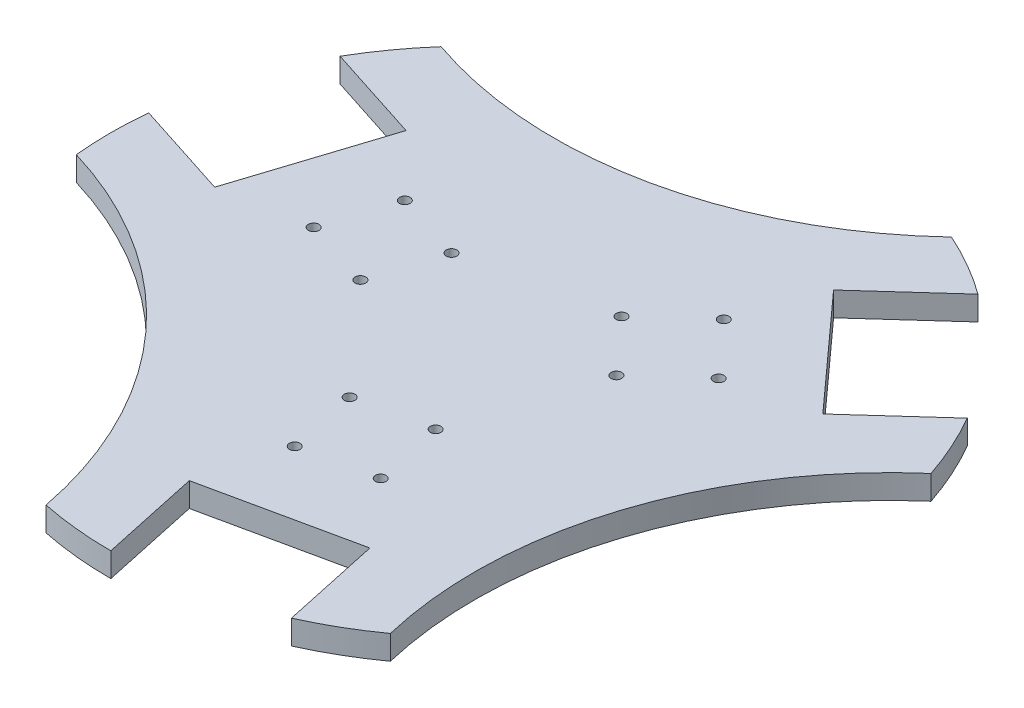
SolidWorks part; units mm, degrees
ref_plane "Plan de face" through (0, 0, 0) normal (0, 0, 1) x (1, 0, 0)
ref_plane "Plan de dessus" through (0, 0, 0) normal (0, 1, 0) x (1, 0, 0)
ref_plane "Plan de droite" through (0, 0, 0) normal (1, 0, 0) x (0, 0, -1)
sketch "Esquisse1" plane through (0, 0, 0) normal (0, 1, 0) x (1, 0, 0)
  line L0 (0.0422, -150) -> (-8.8671, -108.5773)
  line L1 (-8.8671, -108.5773) -> (52.7243, -95.33)
  line L2 (52.7243, -95.33) -> (61.6337, -136.7527)
  line L3 (87.6144, 121.7527) -> (56.196, 93.3256)
  line L4 (56.196, 93.3256) -> (98.4643, 46.6095)
  line L5 (98.4643, 46.6095) -> (129.8827, 75.0366)
  line L6 (-149.2481, 15) -> (-108.9203, 2.0044)
  line L7 (-108.9203, 2.0044) -> (-89.5971, 61.9678)
  line L8 (-89.5971, 61.9678) -> (-129.9249, 74.9634)
  line L9 (-149.2481, -15) -> (-29.8083, -147.0084) construction
  line L10 (87.6144, -121.7527) -> (142.2171, 47.6895) construction
  line L11 (61.6337, 136.7527) -> (-112.4089, 99.3189) construction
  line L12 (-5.571, -45.4334) -> (7.264, -105.1078) construction
  line L13 (21.9286, -101.9536) -> (5.9891, -27.8452) construction
  line L14 (87.394, 58.8446) -> (65.4083, 38.9522) construction
  line L15 (77.3301, 69.9675) -> (55.7445, 50.437) construction
  line L16 (-94.658, 46.2631) -> (-34.9039, 27.0074) construction
  line L17 (-99.2587, 31.9861) -> (-80.0136, 25.7844) construction
  arc A0 (-149.2481, 15) -> (-149.2481, -15) centre (0, 0) ccw
  arc A1 (87.6144, 121.7527) -> (61.6337, 136.7527) centre (0, 0) ccw
  arc A2 (61.6337, -136.7527) -> (87.6144, -121.7527) centre (0, 0) ccw
  arc A3 (87.6144, -121.7527) -> (142.2171, 47.6895) centre (254.8874, -82.1374) cw
  arc A4 (-112.4089, 99.3189) -> (61.6337, 136.7527) centre (-56.3106, 261.8077) ccw
  arc A5 (-29.8083, -147.0084) -> (-149.2481, -15) centre (-198.5768, -179.6703) ccw
  arc A6 (-112.4089, 99.3189) -> (-129.9249, 74.9634) centre (0, 0) ccw
  arc A7 (142.2171, 47.6895) -> (129.8827, 75.0366) centre (0, 0) ccw
  arc A8 (-29.8083, -147.0084) -> (0.0422, -150) centre (0, 0) ccw
  circle A9 centre (-5.571, -45.4334) radius 2.2
  circle A11 centre (0.6634, -74.4196) radius 2.2
  circle A13 centre (29.9927, -68.1113) radius 2.2
  circle A14 centre (23.7582, -39.1252) radius 2.2
  circle A15 centre (41.8718, 17.6566) radius 2.2
  circle A16 centre (64.1175, 37.7843) radius 2.2
  circle A17 centre (43.9898, 60.0301) radius 2.2
  circle A18 centre (21.744, 39.9023) radius 2.2
  circle A19 centre (-36.2269, 27.4337) radius 2.2
  circle A20 centre (-64.7809, 36.6352) radius 2.2
  circle A21 centre (-73.9825, 8.0812) radius 2.2
  circle A22 centre (-45.4284, -1.1203) radius 2.2
  point P3 (0.0422, -150)
  point P4 (61.6337, -136.7527)
  point P5 (129.8827, 75.0366)
  point P6 (87.6144, 121.7527)
  point P7 (-149.2481, 15)
  point P8 (-129.9249, 74.9634)
  point P9 (-29.8083, -147.0084)
  point P10 (87.6144, -121.7527)
  point P11 (142.2171, 47.6895)
  point P12 (61.6337, 136.7527)
  point P13 (-112.4089, 99.3189)
  point P14 (-149.2481, -15)
  point P70 (-108.9203, 2.0044)
  point P71 (0, 0)
  point P72 (-64.7809, 36.6352)
  point P73 (-36.2269, 27.0074)
  point P74 (0.0422, -74.4196)
  point P75 (-5.571, -45.4334)
  point P76 (5.9891, -27.8452)
  point P77 (64.1175, 37.7843)
  point P78 (41.8718, 17.6566)
  dimension "D1" = 300
  dimension "D2" = 63
  dimension "D20" = 171.9
  dimension "D21" = 171.9
  dimension "D22" = 171.9
  dimension "D5" = 4.4
  dimension "D27" = 4.4
  dimension "D28" = 31.39
  dimension "D32" = 4.4
  dimension "D3" = 63
  dimension "D4" = 63
  dimension "D6" = 16.5
  dimension "D7" = 61.039
  dimension "D8" = 30
  dimension "D9" = 30
  dimension "D10" = 30
  dimension "D11" = 30
  dimension "D12" = 30
  dimension "D13" = 30
  dimension "D14" = 63
  dimension "D15" = 42.37
  dimension "D16" = 42.37
  dimension "D17" = 63
  dimension "D18" = 42.37
  dimension "D19" = 63
  dimension "D23" = 31.39
  dimension "D24" = 15
  dimension "D25" = 16.5
  dimension "D26" = 15
  dimension "D29" = 61.39
  dimension "D30" = 16.5
  dimension "D31" = 15
  dimension "D33" = 61.39
  dimension "D34" = 31.39
extrude "Boss.-Extru.1" add sketch "Esquisse1" along normal blind 10
